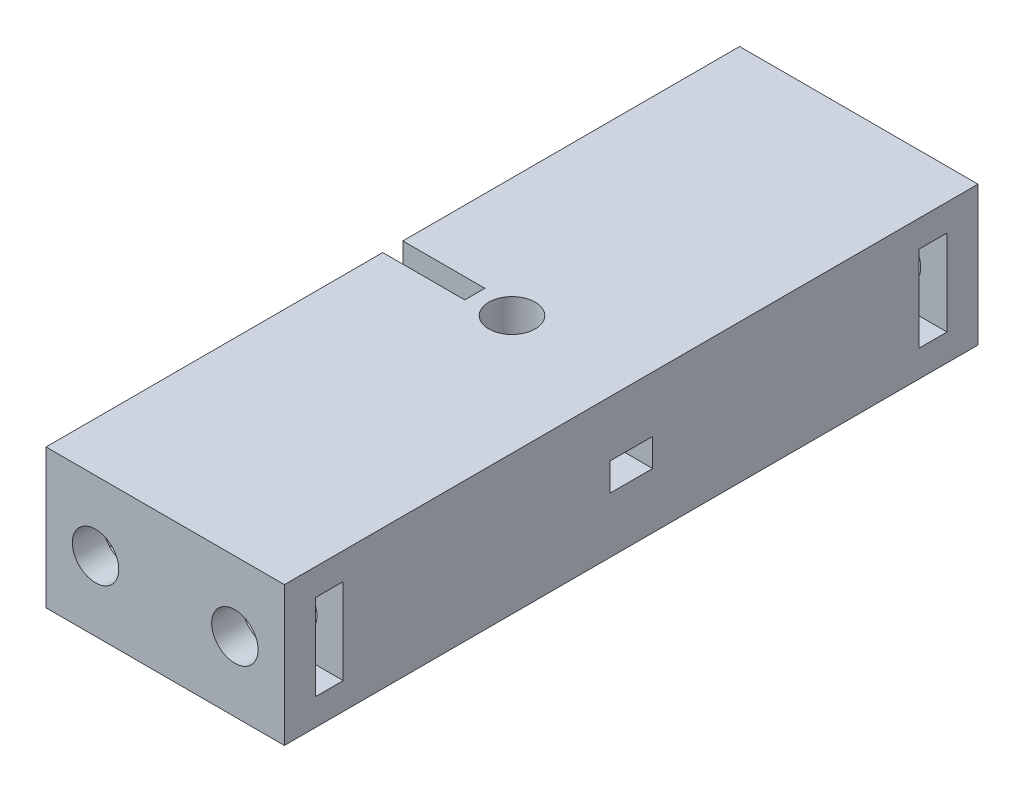
SolidWorks part; units mm, degrees
ref_plane "Front Plane" through (0, 0, 0) normal (0, 0, 1) x (1, 0, 0)
ref_plane "Top Plane" through (0, 0, 0) normal (0, 1, 0) x (1, 0, 0)
ref_plane "Right Plane" through (0, 0, 0) normal (1, 0, 0) x (0, 0, -1)
sketch "Sketch1" plane through (0, 0, 0) normal (0, 0, 1) x (1, 0, 0)
  line L0 (0, 4.5) -> (15.4, 4.5) construction
  line L1 (0, 0) -> (15.4, 0)
  line L2 (0, 0) -> (0, 9)
  line L3 (0, 9) -> (15.4, 9)
  line L4 (15.4, 0) -> (15.4, 9)
  circle A0 centre (3.2, 4.5) radius 1.5
  circle A1 centre (12.2, 4.5) radius 1.5
  point P11 (7.7, 4.5)
  dimension "D3" = 3
  dimension "D4" = 3
  dimension "D1" = 15.4
  dimension "D2" = 9
  dimension "D5" = 4.5
  dimension "D6" = 4.5
extrude "Boss-Extrude1" add sketch "Sketch1" along normal blind 44.8
ref_plane "Plane4" through (0, 0, 2) normal (0, 0, -1) x (-1, 0, 0)
sketch "Sketch2" plane through (0, 0, 2) normal (0, 0, -1) x (-1, 0, 0)
  line L0 (-7.7, 9) -> (-7.7, 0) construction
  line L1 (-0.8, 3.1144) -> (-3.2, 1.7287)
  line L2 (-12.2, 1.7287) -> (-9.8, 3.1144)
  line L3 (-9.8, 3.1144) -> (-9.8, 5.8856)
  line L4 (-9.8, 5.8856) -> (-12.2, 7.2713)
  line L5 (-12.2, 7.2713) -> (-14.6, 5.8856)
  line L6 (-14.6, 5.8856) -> (-14.6, 3.1144)
  line L7 (-15.4, 9) -> (0, 9) construction
  line L8 (0, 0) -> (-15.4, 0) construction
  line L9 (-14.6, 3.1144) -> (-12.2, 1.7287)
  line L10 (-0.8, 5.8856) -> (-0.8, 3.1144)
  line L11 (-3.2, 7.2713) -> (-0.8, 5.8856)
  line L12 (-5.6, 5.8856) -> (-3.2, 7.2713)
  line L13 (-5.6, 3.1144) -> (-5.6, 5.8856)
  line L14 (-3.2, 1.7287) -> (-5.6, 3.1144)
  circle A0 centre (-12.2, 4.5) radius 2.4 construction
  circle A2 centre (-12.2, 4.5) radius 1.5 construction
  circle A3 centre (-3.2, 4.5) radius 2.4 construction
  dimension "D1" = 4.8
extrude "Cut-Extrude1" cut sketch "Sketch2" against normal blind 1.8
ref_plane "Plane1" through (0, 0, 22.4) normal (0, 0, -1) x (-1, 0, 0)
mirror "Mirror1" about plane through (0, 0, 22.4) normal (0, 0, -1) of "Cut-Extrude1"
sketch "Sketch3" plane through (0, 9, 0) normal (0, 1, 0) x (1, 0, 0)
  line L0 (4.95, -22.4) -> (-4.95, -22.4) construction
  line L1 (0, 0) -> (15.4, 0) construction
  line L2 (0, 0) -> (0, -44.8) construction
  line L3 (0, -44.8) -> (15.4, -44.8) construction
  line L4 (15.4, 0) -> (15.4, -44.8) construction
  line L5 (0, 0) -> (15.4, -44.8) construction
  line L6 (0, -44.8) -> (15.4, 0) construction
  line L7 (15.4, -44.8) -> (15.4, 0) construction
  line L8 (15.4, 0) -> (0, 0) construction
  line L9 (0, -44.8) -> (0, 0) construction
  circle A0 centre (7.7, -22.4) radius 1.5
  point P0 (7.7, -22.4)
  dimension "D1" = 3
extrude "Cut-Extrude2" cut sketch "Sketch3" against normal through all
ref_plane "Plane3" through (0, 5.4, 0) normal (0, 1, 0) x (1, 0, 0)
sketch "Sketch4" plane through (0, 5.4, 0) normal (0, 1, 0) x (1, 0, 0)
  line L1 (7.7, -19.6287) -> (5.3, -21.0144)
  line L2 (5.3, -21.0144) -> (5.3, -23.7856)
  line L3 (5.3, -23.7856) -> (7.7, -25.1713)
  line L4 (7.7, -25.1713) -> (10.1, -23.7856)
  line L5 (10.1, -23.7856) -> (10.1, -21.0144)
  line L6 (10.1, -21.0144) -> (7.7, -19.6287)
  circle A0 centre (7.7, -22.4) radius 2.4 construction
  dimension "D1" = 4.8
extrude "Cut-Extrude3" cut sketch "Sketch4" against normal blind 1.8
sketch "Sketch6" plane through (0, 0, 0) normal (-1, 0, 0) x (0, 0, 1)
  line L0 (19.6287, 5.4) -> (25.1713, 5.4)
  line L1 (25.1713, 5.4) -> (25.1713, 3.6)
  line L2 (25.1713, 3.6) -> (19.6287, 3.6)
  line L3 (19.6287, 3.6) -> (19.6287, 5.4)
  point P0 (19.6287, 5.4)
  point P6 (25.1713, 5.4)
  dimension "D1" = 1.8
extrude "Cut-Extrude4" cut sketch "Sketch6" against normal up to vertex (7.7 mm away) up to point (7.7, 5.4, 25.1713)
sketch "Sketch7" plane through (0, 9, 0) normal (0, 1, 0) x (1, 0, 0)
  line L0 (5.3, -21.0144) -> (5.3, -23.7856) construction
  line L1 (5.3, -23.05) -> (0, -23.05)
  line L2 (5.3, -23.05) -> (5.3, -21.75)
  line L3 (5.3, -21.75) -> (0, -21.75)
  line L4 (0, -23.05) -> (0, -21.75)
  line L5 (0, -44.8) -> (0, 0) construction
  line L6 (5.3, -22.4) -> (10.1, -22.4) construction
  line L7 (10.1, -23.7856) -> (10.1, -21.0144) construction
  dimension "D1" = 1.3
extrude "Cut-Extrude5" cut sketch "Sketch7" against normal up to next
sketch "Sketch8" plane through (10.1, 0, 0) normal (-1, 0, 0) x (0, 0, 1)
  line L0 (23.7856, 5.4) -> (21.0144, 5.4) construction
  line L1 (21.0144, 3.6) -> (23.7856, 3.6)
  line L2 (21.0144, 3.6) -> (21.0144, 5.4)
  line L3 (21.0144, 5.4) -> (23.7856, 5.4)
  line L4 (23.7856, 3.6) -> (23.7856, 5.4)
  line L5 (23.7856, 3.6) -> (23.7856, 5.4) construction
extrude "Cut-Extrude6" cut sketch "Sketch8" against normal through all
sketch "Sketch10" plane through (15.4, 0, 0) normal (1, 0, 0) x (0, 0, -1)
  line L0 (-2, 7.2713) -> (-2, 1.7287)
  line L1 (-2, 1.7287) -> (-3.8, 1.7287)
  line L2 (-3.8, 1.7287) -> (-3.8, 7.2713)
  line L3 (-3.8, 7.2713) -> (-2, 7.2713)
  point P0 (-2, 7.2713)
  point P2 (-2, 1.7287)
  dimension "D1" = 1.8
extrude "Cut-Extrude7" cut sketch "Sketch10" against normal up to vertex (3.2 mm away) up to point (12.2, 7.2713, 2)
ref_plane "Plane5" through (7.7, 0, 0) normal (1, 0, 0) x (0, 0, -1)
mirror "Mirror2" about plane through (7.7, 0, 0) normal (1, 0, 0) of "Cut-Extrude7"
sketch "Sketch11" plane through (9.8, 0, 0) normal (1, 0, 0) x (0, 0, -1)
  line L1 (-3.8, 3.1144) -> (-2, 3.1144)
  line L2 (-3.8, 3.1144) -> (-3.8, 5.8856)
  line L3 (-3.8, 5.8856) -> (-2, 5.8856)
  line L4 (-2, 3.1144) -> (-2, 5.8856)
extrude "Cut-Extrude8" cut sketch "Sketch11" against normal through all
ref_plane "Plane6" through (0, 0, 22.4) normal (0, 0, -1) x (-1, 0, 0)
mirror "Mirror3" about plane through (0, 0, 22.4) normal (0, 0, -1) of "Cut-Extrude7", "Cut-Extrude8", "Mirror2"
